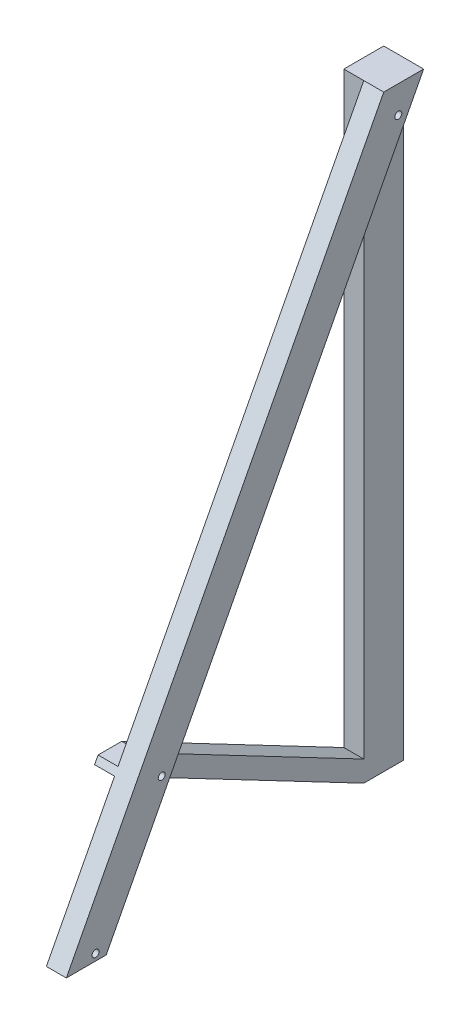
SolidWorks part; units mm, degrees
ref_plane "Front Plane" through (0, 0, 0) normal (0, 0, 1) x (1, 0, 0)
ref_plane "Top Plane" through (0, 0, 0) normal (0, 1, 0) x (1, 0, 0)
ref_plane "Right Plane" through (0, 0, 0) normal (1, 0, 0) x (0, 0, -1)
sketch "Sketch1" plane through (0, 0, 0) normal (1, 0, 0) x (0, 0, -1)
  line L0 (0, 0) -> (0, 774.7)
  line L1 (0, 774.7) -> (-404.0996, 0)
  line L2 (-404.0996, 0) -> (0, 0)
  line L3 (0, 0) -> (-317.6663, 165.7013)
  line L4 (0, 774.7) -> (-50.8, 774.7)
  line L5 (-50.8, 774.7) -> (-454.8996, 0)
  line L6 (-454.8996, 0) -> (-404.0996, 0)
  dimension "D1" = 873.76
  dimension "D2" = 774.7
  dimension "D3" = 50.8
extrude "Boss-Extrude1" add sketch "Sketch1" along normal blind 25.4 contours L5 L6 L1 L4
sketch "Sketch2" plane through (0, 0, 0) normal (1, 0, 0) x (0, 0, -1)
  line L0 (0, 0) -> (-333.4825, 174.895)
  line L1 (-333.4825, 174.895) -> (-363.6707, 174.895)
  line L2 (-368.0981, 166.4071) -> (-50.8, 0)
  line L3 (-50.8, 0) -> (0, 0)
  line L4 (-50.8, 774.7) -> (-454.8996, 0) construction
  line L5 (-363.6707, 174.895) -> (-368.0981, 166.4071)
  circle A0 centre (-333.4825, 161.7725) radius 4.3896
  point P4 (-363.6707, 174.895)
  point P7 (-333.4825, 161.7725)
extrude "Boss-Extrude4" add sketch "Sketch2" against normal blind 25.4
sketch "Sketch4" plane through (0, 0, 0) normal (-1, 0, 0) x (0, 0, 1)
  circle A1 centre (333.4825, 161.7725) radius 4.3896
  circle A2 centre (333.4825, 161.7725) radius 4.3896
  dimension "D1" = 0
extrude "Cut-Extrude1" cut sketch "Sketch4" against normal up to surface (25.4 mm away) up to face at (25.4, 387.35, 227.4498)
sketch "Sketch6" plane through (0, 0, 0) normal (-1, 0, 0) x (0, 0, 1)
  circle A0 centre (417.6601, 8.4006) radius 4.445
  point P2 (417.6601, 8.4006)
  dimension "D1" = 8.89
extrude "Cut-Extrude2" cut sketch "Sketch6" against normal blind 25.4
sketch "Sketch7" plane through (0, 0, 0) normal (-1, 0, 0) x (0, 0, 1)
  line L1 (0, 0) -> (50.8, 0)
  line L2 (0, 0) -> (0, 774.7)
  line L3 (0, 774.7) -> (50.8, 774.7)
  line L4 (50.8, 0) -> (50.8, 774.7)
  dimension "D1" = 50.8
  dimension "D2" = 774.7
extrude "Boss-Extrude5" add sketch "Sketch7" along normal up to surface (25.4 mm away) up to face at (-25.4, 161.7725, 329.0929)
sketch "Sketch8" plane through (25.4, 0, 0) normal (1, 0, 0) x (0, 0, -1)
  circle A0 centre (-32.2539, 739.883) radius 4.445
  point P2 (-27.7538, 603.619)
  point P3 (-32.2539, 739.883)
  dimension "D1" = 8.89
extrude "Cut-Extrude3" cut sketch "Sketch8" against normal up to surface (50.8 mm away) up to face at (-25.4, 261.5299, 152.2064)
